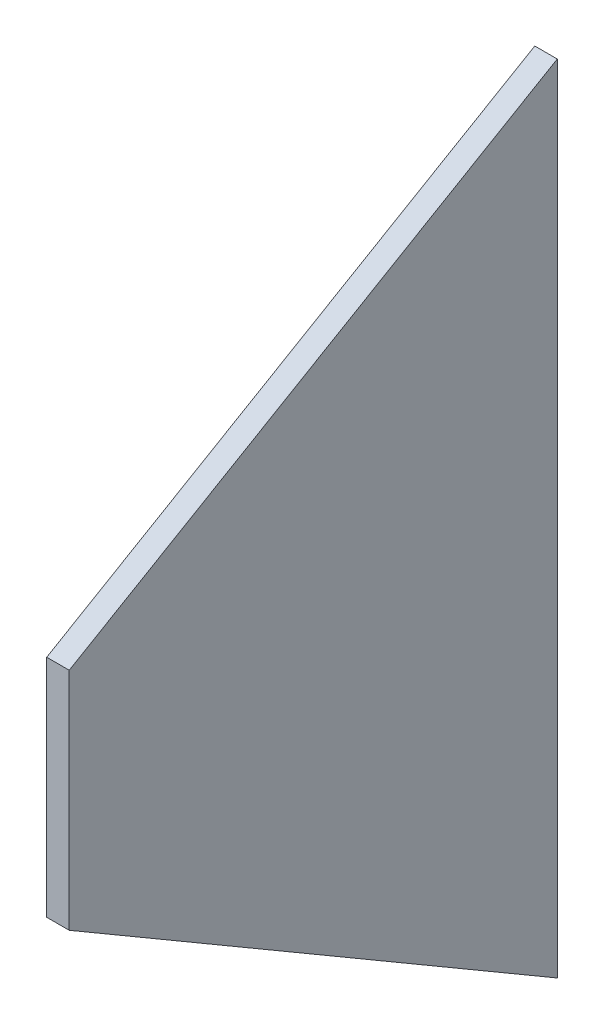
SolidWorks part; units mm, degrees
material "Balsa"
ref_plane "Front Plane" through (0, 0, 0) normal (1, 0, 0) x (0, 1, 0)
ref_plane "Top Plane" through (0, 0, 0) normal (0, 0, 1) x (0, 1, 0)
ref_plane "Right Plane" through (0, 0, 0) normal (0, 1, 0) x (-1, 0, 0)
sketch "Sketch1" plane through (0, 0, 0) normal (1, 0, 0) x (0, 1, 0)
  line L0 (0, 0) -> (106, 0)
  line L1 (106, 0) -> (68, 65)
  line L2 (68, 65) -> (38, 65)
  line L3 (38, 65) -> (0, 0)
  point P3 (53, 0)
  point P6 (53, 65)
  dimension "D1" = 106
  dimension "D2" = 30
  dimension "D3" = 65
extrude "Boss-Extrude1" add sketch "Sketch1" along normal blind 3
